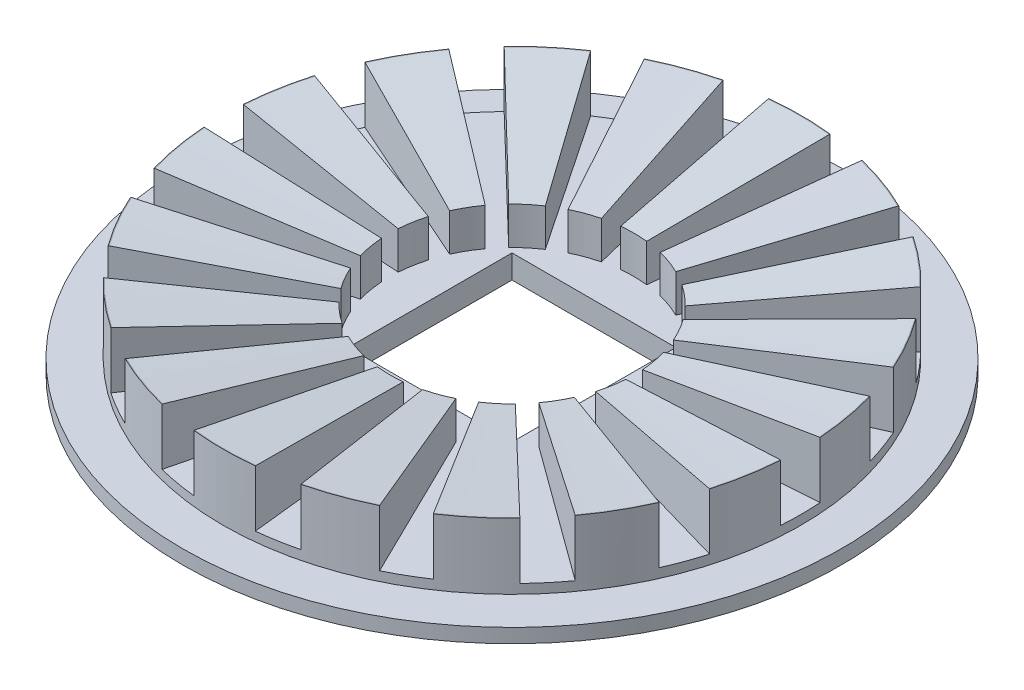
SolidWorks part; units mm, degrees
ref_plane "Front Plane" through (0, 0, 0) normal (0, 0, 1) x (1, 0, 0)
ref_plane "Top Plane" through (0, 0, 0) normal (0, 1, 0) x (1, 0, 0)
ref_plane "Right Plane" through (0, 0, 0) normal (1, 0, 0) x (0, 0, -1)
ref_plane "Plane1" through (0, 3.25, 0) normal (0, 1, 0) x (1, 0, 0)
sketch "Sketch1" plane through (0, 0, 0) normal (0, 1, 0) x (1, 0, 0)
  circle A1 centre (0, 0) radius 17.5
  circle A2 centre (0, 0) radius 15.35
  dimension "D1" = 35
  dimension "D2" = 2.15
sketch "Sketch2" plane through (0, 0, 0) normal (0, 1, 0) x (1, 0, 0)
  circle A1 centre (0, 0) radius 15.35
  circle A2 centre (0, 0) radius 15.35 construction
sketch "Sketch5" plane through (0, 0, 0) normal (0, 1, 0) x (-1, 0, 0)
  line L1 (-4.35, 4.35) -> (4.35, 4.35)
  line L2 (-4.35, 4.35) -> (-4.35, -4.35)
  line L3 (-4.35, -4.35) -> (4.35, -4.35)
  line L4 (4.35, 4.35) -> (4.35, -4.35)
  line L5 (-4.35, 4.35) -> (4.35, -4.35) construction
  line L6 (-4.35, -4.35) -> (4.35, 4.35) construction
  dimension "D1" = 8.7
sketch "Sketch6" plane through (0, 3.25, 0) normal (0, 1, 0) x (1, 0, 0)
  circle A0 centre (0, 0) radius 6.5 construction
  dimension "D1" = 13
sketch "Sketch3" plane through (0, 0, 0) normal (0, 1, 0) x (1, 0, 0)
  line L0 (0, 15.35) -> (0, 0) construction
  line L1 (0, 0) -> (0.6907, 6.4632) construction
  line L2 (-1.6312, 15.2631) -> (-0.6907, 6.4632)
  line L3 (-0.6907, 6.4632) -> (0, 0) construction
  line L4 (0.6907, 6.4632) -> (1.6312, 15.2631)
  line L5 (3.6875, 14.9005) -> (1.5615, 6.3097)
  line L6 (2.8596, 5.8372) -> (6.7531, 13.7847)
  line L7 (8.5614, 12.7407) -> (3.6253, 5.3951)
  line L8 (4.6836, 4.5071) -> (11.0605, 10.6437)
  line L9 (12.4026, 9.0442) -> (5.2519, 3.8298)
  line L10 (5.9427, 2.6334) -> (14.0338, 6.2189)
  line L11 (14.748, 4.2568) -> (6.2451, 1.8025)
  line L12 (6.4849, 0.4421) -> (15.3145, 1.044)
  line L13 (15.3145, -1.044) -> (6.4849, -0.4421)
  line L14 (6.2451, -1.8025) -> (14.748, -4.2568)
  line L15 (14.0338, -6.2189) -> (5.9427, -2.6334)
  line L16 (5.2519, -3.8298) -> (12.4026, -9.0442)
  line L17 (11.0605, -10.6437) -> (4.6836, -4.5071)
  line L18 (3.6253, -5.3951) -> (8.5614, -12.7407)
  line L19 (6.7531, -13.7847) -> (2.8596, -5.8372)
  line L20 (1.5615, -6.3097) -> (3.6875, -14.9005)
  line L21 (1.6312, -15.2631) -> (0.6907, -6.4632)
  line L22 (-0.6907, -6.4632) -> (-1.6312, -15.2631)
  line L23 (-3.6875, -14.9005) -> (-1.5615, -6.3097)
  line L24 (-2.8596, -5.8372) -> (-6.7531, -13.7847)
  line L25 (-8.5614, -12.7407) -> (-3.6253, -5.3951)
  line L26 (-4.6836, -4.5071) -> (-11.0605, -10.6437)
  line L27 (-12.4026, -9.0442) -> (-5.2519, -3.8298)
  line L28 (-5.9427, -2.6334) -> (-14.0338, -6.2189)
  line L29 (-14.748, -4.2568) -> (-6.2451, -1.8025)
  line L30 (-6.4849, -0.4421) -> (-15.3145, -1.044)
  line L31 (-15.3145, 1.044) -> (-6.4849, 0.4421)
  line L32 (-6.2451, 1.8025) -> (-14.748, 4.2568)
  line L33 (-14.0338, 6.2189) -> (-5.9427, 2.6334)
  line L34 (-5.2519, 3.8298) -> (-12.4026, 9.0442)
  line L35 (-11.0605, 10.6437) -> (-4.6836, 4.5071)
  line L36 (-3.6253, 5.3951) -> (-8.5614, 12.7407)
  line L37 (-6.7531, 13.7847) -> (-2.8596, 5.8372)
  line L38 (-1.5615, 6.3097) -> (-3.6875, 14.9005)
  circle A0 centre (0, 0) radius 15.35 construction
  arc A2 (0.6907, 6.4632) -> (-0.6907, 6.4632) centre (0, 0) ccw
  arc A3 (1.6312, 15.2631) -> (-1.6312, 15.2631) centre (0, 0) ccw
  arc A4 (2.8596, 5.8372) -> (1.5615, 6.3097) centre (0, 0) ccw
  arc A5 (6.7531, 13.7847) -> (3.6875, 14.9005) centre (0, 0) ccw
  arc A6 (4.6836, 4.5071) -> (3.6253, 5.3951) centre (0, 0) ccw
  arc A7 (11.0605, 10.6437) -> (8.5614, 12.7407) centre (0, 0) ccw
  arc A8 (5.9427, 2.6334) -> (5.2519, 3.8298) centre (0, 0) ccw
  arc A9 (14.0338, 6.2189) -> (12.4026, 9.0442) centre (0, 0) ccw
  arc A10 (6.4849, 0.4421) -> (6.2451, 1.8025) centre (0, 0) ccw
  arc A11 (15.3145, 1.044) -> (14.748, 4.2568) centre (0, 0) ccw
  arc A12 (6.2451, -1.8025) -> (6.4849, -0.4421) centre (0, 0) ccw
  arc A13 (14.748, -4.2568) -> (15.3145, -1.044) centre (0, 0) ccw
  arc A14 (5.2519, -3.8298) -> (5.9427, -2.6334) centre (0, 0) ccw
  arc A15 (12.4026, -9.0442) -> (14.0338, -6.2189) centre (0, 0) ccw
  arc A16 (3.6253, -5.3951) -> (4.6836, -4.5071) centre (0, 0) ccw
  arc A17 (8.5614, -12.7407) -> (11.0605, -10.6437) centre (0, 0) ccw
  arc A18 (1.5615, -6.3097) -> (2.8596, -5.8372) centre (0, 0) ccw
  arc A19 (3.6875, -14.9005) -> (6.7531, -13.7847) centre (0, 0) ccw
  arc A20 (-0.6907, -6.4632) -> (0.6907, -6.4632) centre (0, 0) ccw
  arc A21 (-1.6312, -15.2631) -> (1.6312, -15.2631) centre (0, 0) ccw
  arc A22 (-2.8596, -5.8372) -> (-1.5615, -6.3097) centre (0, 0) ccw
  arc A23 (-6.7531, -13.7847) -> (-3.6875, -14.9005) centre (0, 0) ccw
  arc A24 (-4.6836, -4.5071) -> (-3.6253, -5.3951) centre (0, 0) ccw
  arc A25 (-11.0605, -10.6437) -> (-8.5614, -12.7407) centre (0, 0) ccw
  arc A26 (-5.9427, -2.6334) -> (-5.2519, -3.8298) centre (0, 0) ccw
  arc A27 (-14.0338, -6.2189) -> (-12.4026, -9.0442) centre (0, 0) ccw
  arc A28 (-6.4849, -0.4421) -> (-6.2451, -1.8025) centre (0, 0) ccw
  arc A29 (-15.3145, -1.044) -> (-14.748, -4.2568) centre (0, 0) ccw
  arc A30 (-6.2451, 1.8025) -> (-6.4849, 0.4421) centre (0, 0) ccw
  arc A31 (-14.748, 4.2568) -> (-15.3145, 1.044) centre (0, 0) ccw
  arc A32 (-5.2519, 3.8298) -> (-5.9427, 2.6334) centre (0, 0) ccw
  arc A33 (-12.4026, 9.0442) -> (-14.0338, 6.2189) centre (0, 0) ccw
  arc A34 (-3.6253, 5.3951) -> (-4.6836, 4.5071) centre (0, 0) ccw
  arc A35 (-8.5614, 12.7407) -> (-11.0605, 10.6437) centre (0, 0) ccw
  arc A36 (-1.5615, 6.3097) -> (-2.8596, 5.8372) centre (0, 0) ccw
  arc A37 (-3.6875, 14.9005) -> (-6.7531, 13.7847) centre (0, 0) ccw
  circle A39 centre (0, 0) radius 6.5 construction
  point P7 (0, 0)
  point P8 (0, 0)
  point P10 (0, 0)
  point P82 (0, 0)
  point P83 (0, 0)
  dimension "D1" = 12.2
  dimension "D2" = 6.1
  dimension "D3" = 18
extrude "Boss-Extrude3" add sketch "Sketch2" along normal blind 1.25
extrude "Cut-Extrude3" cut sketch "Sketch5" along normal blind 1.25
extrude "Boss-Extrude4" add sketch "Sketch3" along normal blind 4.25
sketch "Sketch7" plane through (0, 0, 0) normal (0, 0, 1) x (1, 0, 0)
  line L0 (6.5, 3.25) -> (15.3145, 4.25)
  line L1 (6.5, 3.25) -> (-6.5, 3.25) construction
  line L2 (15.3145, 4.25) -> (6.5, 4.25)
  line L3 (6.5, 4.25) -> (6.5, 3.25)
  line L4 (14.0338, 4.25) -> (12.4026, 4.25) construction
  line L5 (15.3145, 4.25) -> (15.3145, 1.25) construction
  point P7 (0, 0)
ref_axis "Axis1" through (0, 3.25, 0) along (0, 1, 0)
revolve "Cut-Revolve1" cut sketch "Sketch7" angle 360 about axis through (0, 3.25, 0) along (0, 1, 0)
extrude "Boss-Extrude5" add sketch "Sketch1" along normal blind 0.75
sketch "Sketch8" plane through (0, 0, 0) normal (0, 1, 0) x (1, 0, 0)
  line L0 (0, -32.8799) -> (0, 23.2086) construction
  line L5 (-12.5, -14.65) -> (12.5, -14.65) construction
  line L6 (-12.5, -14.65) -> (-12.5, 9.35) construction
  line L7 (-12.5, 9.35) -> (12.5, 9.35) construction
  line L8 (12.5, -14.65) -> (12.5, 9.35) construction
  line L9 (20.7069, 0) -> (-21.9339, 0) construction
  line L10 (4.35, 4.35) -> (-4.35, 4.35) construction
  circle A0 centre (-10.8, 0) radius 0.8
  circle A1 centre (10.8, 0) radius 0.8
  circle A5 centre (-10.8, 0) radius 2
  circle A6 centre (10.8, 0) radius 2
  point P26 (0, -14.65)
  dimension "D4" = 1.6
  dimension "D6" = 4
  dimension "D1" = 25
  dimension "D2" = 24
  dimension "D3" = 5
  dimension "D5" = 1.7
extrude "Boss-Extrude6" add sketch "Sketch8" against normal blind 1
